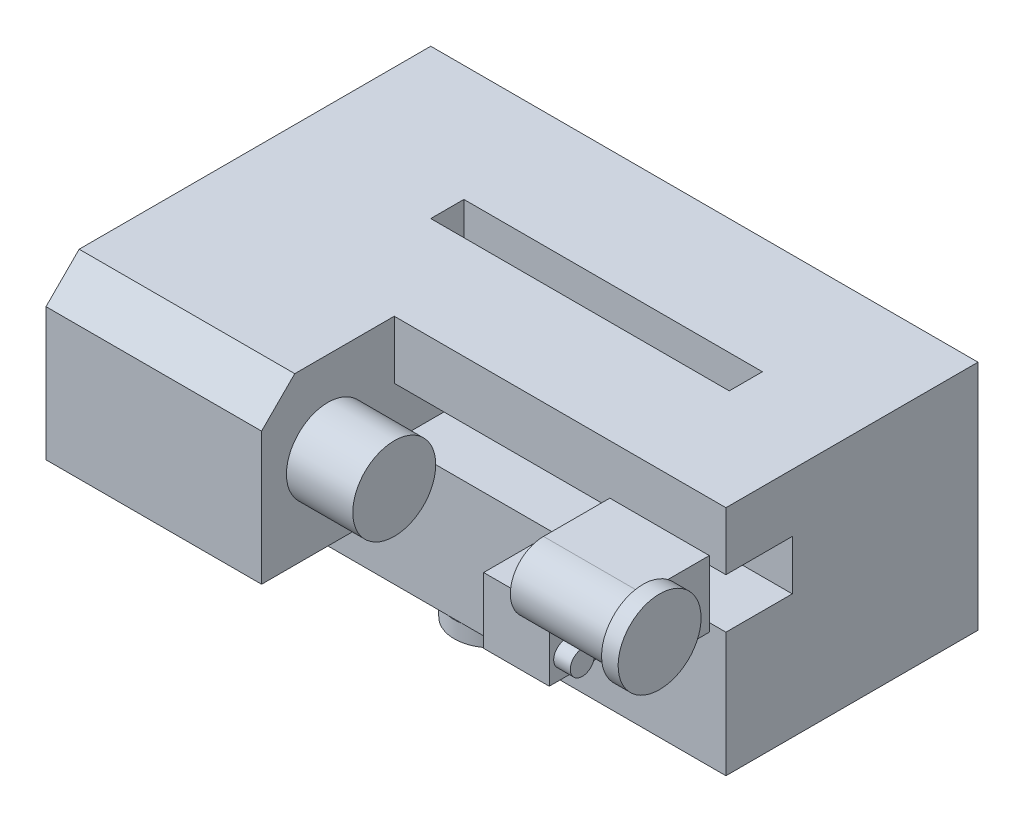
SolidWorks part; units mm, degrees
ref_plane "正面" through (0, 0, 0) normal (0, 0, 1) x (1, 0, 0)
ref_plane "平面" through (0, 0, 0) normal (0, 1, 0) x (1, 0, 0)
ref_plane "右側面" through (0, 0, 0) normal (1, 0, 0) x (0, 0, -1)
sketch "ｽｹｯﾁ1" plane through (0, 0, 0) normal (0, 0, 1) x (1, 0, 0)
  line L1 (-62.8461, 58.2529) -> (102.1539, 58.2529)
  line L2 (-62.8461, 58.2529) -> (-62.8461, -11.7471)
  line L3 (-62.8461, -11.7471) -> (102.1539, -11.7471)
  line L4 (102.1539, 58.2529) -> (102.1539, -11.7471)
  dimension "D1" = 165
  dimension "D2" = 70
extrude "ﾎﾞｽ - 押し出し1" add sketch "ｽｹｯﾁ1" along normal blind 116
sketch "ｽｹｯﾁ2" plane through (0, -11.7471, 0) normal (0, -1, 0) x (-1, 0, 0)
  line L1 (-102.1539, -116) -> (-2.1539, -116)
  line L2 (-102.1539, -116) -> (-102.1539, -76)
  line L3 (-102.1539, -76) -> (-2.1539, -76)
  line L4 (-2.1539, -116) -> (-2.1539, -76)
  dimension "D1" = 40
  dimension "D2" = 100
extrude "ｶｯﾄ - 押し出し1" cut sketch "ｽｹｯﾁ2" against normal through all
sketch "ｽｹｯﾁ3" plane through (-62.8461, 0, 0) normal (-1, 0, 0) x (0, 0, 1)
  line L0 (116, -11.7471) -> (116, 8.2529)
  line L1 (116, 58.2529) -> (116, -11.7471) construction
  line L2 (116, 8.2529) -> (86, -11.7471)
  line L3 (116, -11.7471) -> (0, -11.7471) construction
  line L4 (116, -11.7471) -> (86, -11.7471)
  line L5 (116, 58.2529) -> (106, 58.2529)
  line L6 (116, 58.2529) -> (0, 58.2529) construction
  line L7 (106, 58.2529) -> (116, 48.2529)
  line L8 (116, 48.2529) -> (116, 58.2529)
  dimension "D1" = 30
  dimension "D2" = 20
  dimension "D3" = 45
  dimension "D4" = 10
extrude "ｶｯﾄ - 押し出し2" cut sketch "ｽｹｯﾁ3" against normal blind 70
sketch "ｽｹｯﾁ4" plane through (0, 0, 116) normal (0, 0, 1) x (1, 0, 0)
  line L0 (2.1539, 8.2529) -> (-62.8461, 8.2529) construction
  line L1 (-47.3322, 8.2529) -> (2.1539, 8.2529)
  line L2 (-47.3322, 8.2529) -> (-47.3322, -11.7471)
  line L3 (-47.3322, -11.7471) -> (2.1539, -11.7471)
  line L4 (2.1539, 8.2529) -> (2.1539, -11.7471)
extrude "ｶｯﾄ - 押し出し3" cut sketch "ｽｹｯﾁ4" against normal blind 40
sketch "ｽｹｯﾁ5" plane through (0, -11.7471, 0) normal (0, -1, 0) x (-1, 0, 0)
  line L0 (62.8461, 0) -> (-102.1539, 0) construction
  line L1 (25.3461, 0) -> (-64.6539, 0)
  line L2 (25.3461, 0) -> (25.3461, -20)
  line L3 (25.3461, -20) -> (-64.6539, -20)
  line L4 (-64.6539, 0) -> (-64.6539, -20)
  line L5 (-102.1539, -76) -> (-102.1539, 0) construction
  dimension "D1" = 90
  dimension "D2" = 37.5
  dimension "D3" = 20
extrude "ｶｯﾄ - 押し出し4" cut sketch "ｽｹｯﾁ5" against normal blind 20
sketch "ｽｹｯﾁ6" plane through (2.1539, 0, 0) normal (1, 0, 0) x (0, 0, -1)
  line L0 (-116, 48.2529) -> (-116, 8.2529) construction
  line L1 (-106, 58.2529) -> (-76, 58.2529) construction
  circle A0 centre (-96, 33.2529) radius 12.5
  dimension "D1" = 25
  dimension "D2" = 20
  dimension "D3" = 25
extrude "ﾎﾞｽ - 押し出し2" add sketch "ｽｹｯﾁ6" along normal blind 20
sketch "ｽｹｯﾁ7" plane through (0, 0, 76) normal (0, 0, 1) x (1, 0, 0)
  line L0 (2.1539, 58.2529) -> (2.1539, 8.2529) construction
  line L1 (2.1539, 25.7529) -> (102.1539, 25.7529)
  line L2 (2.1539, 25.7529) -> (2.1539, 40.7529)
  line L3 (2.1539, 40.7529) -> (102.1539, 40.7529)
  line L4 (102.1539, 25.7529) -> (102.1539, 40.7529)
  line L5 (102.1539, 58.2529) -> (102.1539, -11.7471) construction
  line L6 (2.1539, 58.2529) -> (102.1539, 58.2529) construction
  dimension "D1" = 15
  dimension "D2" = 17.5
extrude "ｶｯﾄ - 押し出し5" cut sketch "ｽｹｯﾁ7" against normal blind 20
sketch "ｽｹｯﾁ8" plane through (0, 0, 76) normal (0, 0, 1) x (1, 0, 0)
  line L0 (2.1539, 25.7529) -> (102.1539, 25.7529) construction
  line L1 (97.1539, 23.2529) -> (67.1539, 23.2529)
  line L2 (97.1539, 23.2529) -> (97.1539, 43.2529)
  line L3 (97.1539, 43.2529) -> (67.1539, 43.2529)
  line L4 (67.1539, 23.2529) -> (67.1539, 43.2529)
  line L5 (102.1539, 25.7529) -> (102.1539, 40.7529) construction
  dimension "D1" = 20
  dimension "D2" = 2.5
  dimension "D3" = 30
  dimension "D4" = 5
extrude "ﾎﾞｽ - 押し出し3" add sketch "ｽｹｯﾁ8" along normal blind 30
sketch "ｽｹｯﾁ9" plane through (97.1539, 0, 0) normal (1, 0, 0) x (0, 0, -1)
  line L0 (-96, 43.2529) -> (-106, 43.2529)
  line L1 (-106, 43.2529) -> (-106, 23.2529)
  line L2 (-96, 23.2529) -> (-106, 23.2529)
  arc A0 (-96, 43.2529) -> (-96, 23.2529) centre (-96, 33.2529) ccw
  line M4 (-76, 43.2529) -> (-106, 43.2529)
  line M5 (-106, 43.2529) -> (-106, 23.2529)
  line M6 (-106, 23.2529) -> (-76, 23.2529)
  dimension "D1" = 20
extrude "ｶｯﾄ - 押し出し6" cut sketch "ｽｹｯﾁ9" against normal blind 30 contours A0 M4 M5 | A0 L1 M6
sketch "ｽｹｯﾁ10" plane through (97.1539, 0, 0) normal (1, 0, 0) x (0, 0, -1)
  circle A0 centre (-96, 33.2529) radius 12.5
extrude "ﾎﾞｽ - 押し出し5" add sketch "ｽｹｯﾁ10" along normal blind 5
sketch "ｽｹｯﾁ11" plane through (0, -11.7471, 0) normal (0, -1, 0) x (1, 0, 0)
  line L0 (102.1539, 76) -> (102.1539, 0) construction
  line L1 (-17.8461, 45) -> (72.1539, 45)
  line L2 (-17.8461, 45) -> (-17.8461, 35)
  line L3 (-17.8461, 35) -> (72.1539, 35)
  line L4 (72.1539, 45) -> (72.1539, 35)
  line L5 (64.6539, 20) -> (-25.3461, 20) construction
  dimension "D1" = 30
  dimension "D2" = 90
  dimension "D3" = 10
  dimension "D4" = 15
extrude "ｶｯﾄ - 押し出し7" cut sketch "ｽｹｯﾁ11" against normal through all
sketch "ｽｹｯﾁ12" plane through (0, 0, 76) normal (0, 0, 1) x (1, 0, 0)
  line L1 (44.0987, 19.8044) -> (63.8919, 19.8044)
  line L2 (44.0987, 19.8044) -> (44.0987, 0)
  line L3 (44.0987, 0) -> (63.8919, 0)
  line L4 (63.8919, 19.8044) -> (63.8919, 0)
extrude "ﾎﾞｽ - 押し出し6" add sketch "ｽｹｯﾁ12" along normal blind 15
sketch "ｽｹｯﾁ13" plane through (0, -11.7471, 0) normal (0, -1, 0) x (-1, 0, 0)
  circle A0 centre (-20.4718, -64.8446) radius 11.3569
  circle A1 centre (-48.3791, -62.3432) radius 5.8499
extrude "ﾎﾞｽ - 押し出し7" add sketch "ｽｹｯﾁ13" along normal blind 5
sketch "ｽｹｯﾁ14" plane through (63.8919, 0, 0) normal (1, 0, 0) x (0, 0, -1)
  circle A0 centre (-86.0373, 6.2363) radius 3.6361
extrude "ﾎﾞｽ - 押し出し8" add sketch "ｽｹｯﾁ14" along normal blind 5
scale "ｽｹｰﾙ1" scale about centroid uniform scaling yes scale factor 10
